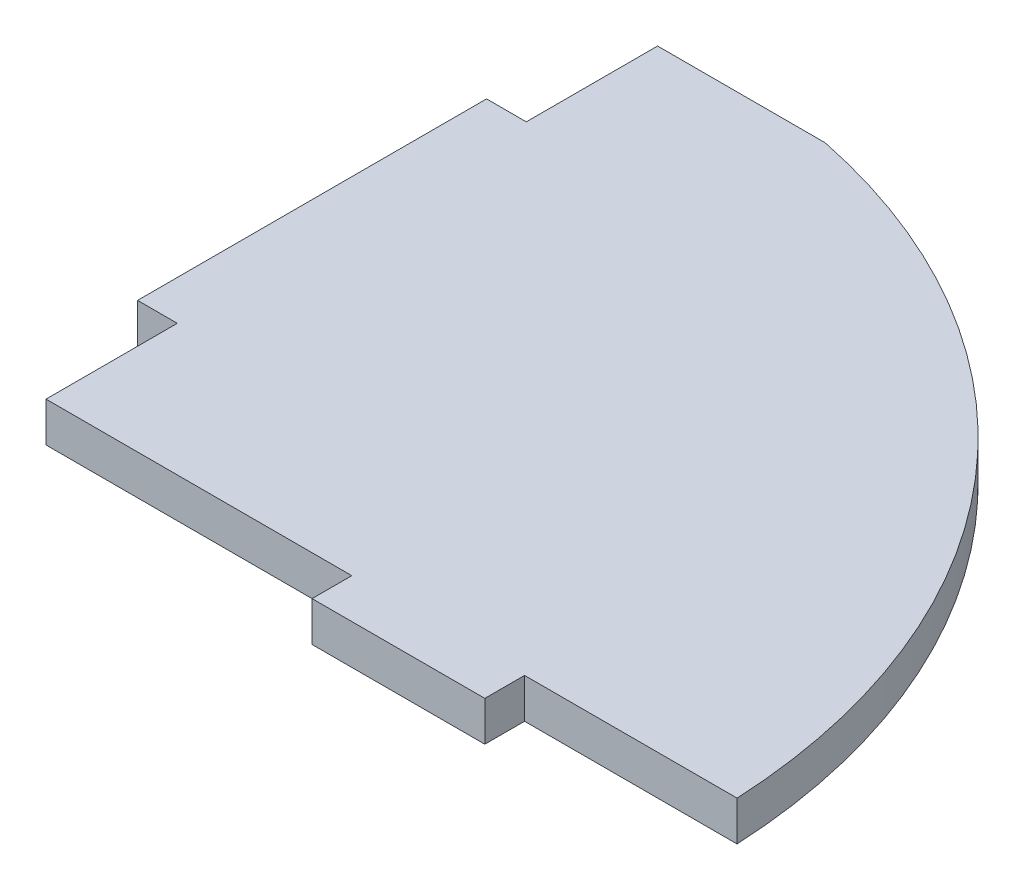
SolidWorks part; units mm, degrees
ref_plane "Front Plane" through (0, 0, 0) normal (0, 0, 1) x (1, 0, 0)
ref_plane "Top Plane" through (0, 0, 0) normal (0, 1, 0) x (1, 0, 0)
ref_plane "Right Plane" through (0, 0, 0) normal (1, 0, 0) x (0, 0, -1)
sketch "Sketch2" plane through (0, 0, 0) normal (0, 1, 0) x (1, 0, 0)
  line L0 (35.179, 0) -> (50.8, 0)
  line L1 (0, 0) -> (22.479, 0)
  line L2 (0, 0) -> (0, 9.652)
  line L3 (0, 44.958) -> (12.319, 44.958)
  line L4 (0, 35.306) -> (0, 44.958)
  line L6 (35.179, 0) -> (35.179, -2.921)
  line L7 (35.179, -2.921) -> (22.479, -2.921)
  line L8 (22.479, 0) -> (22.479, -2.921)
  line L9 (0, 9.652) -> (-2.921, 9.652)
  line L10 (-2.921, 35.306) -> (-2.921, 9.652)
  line L11 (0, 35.306) -> (-2.921, 35.306)
  arc A0 (12.319, 44.958) -> (50.8, 0) centre (2.5633, -2.3398) cw
  point P5 (12.319, 44.958)
  dimension "D1" = 25.654
  dimension "D2" = 44.958
  dimension "D3" = 12.319
  dimension "D4" = 9.652
  dimension "D5" = 9.652
  dimension "D6" = 22.479
  dimension "D7" = 12.7
  dimension "D8" = 2.921
extrude "Boss-Extrude1" add sketch "Sketch2" along normal blind 2.921
